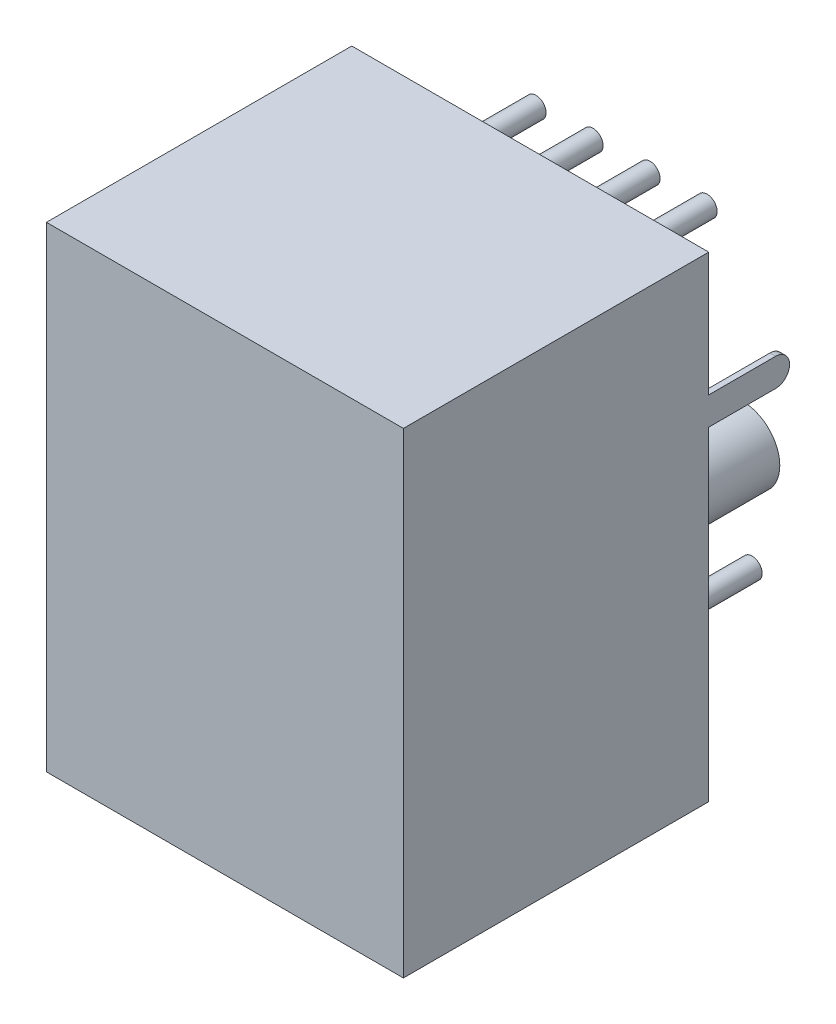
SolidWorks part; units mm, degrees
ref_plane "Front Plane" through (0, 0, 0) normal (0, 0, 1) x (1, 0, 0)
ref_plane "Top Plane" through (0, 0, 0) normal (0, 1, 0) x (1, 0, 0)
ref_plane "Right Plane" through (0, 0, 0) normal (1, 0, 0) x (0, 0, -1)
sketch "Sketch1" plane through (0, 0, 0) normal (0, 1, 0) x (1, 0, 0)
  line L1 (0, 0) -> (15.9, 0)
  line L2 (0, 0) -> (0, 13.6)
  line L3 (0, 13.6) -> (15.9, 13.6)
  line L4 (15.9, 0) -> (15.9, 13.6)
  dimension "D1" = 13.6
  dimension "D2" = 15.9
extrude "Boss-Extrude1" add sketch "Sketch1" along normal blind 21.2
sketch "Sketch2" plane through (0, 0, -13.6) normal (0, 0, -1) x (-1, 0, 0)
  line L0 (-15.9, 0) -> (0, 0) construction
  line L1 (-13.665, 10.8) -> (-2.235, 10.8) construction
  line L2 (-7.95, 0) -> (-7.95, 10.8) construction
  circle A0 centre (-13.665, 10.8) radius 1.65
  circle A1 centre (-2.235, 10.8) radius 1.65
  dimension "D3" = 3.3
  dimension "D1" = 10.8
  dimension "D2" = 11.43
extrude "Boss-Extrude2" add sketch "Sketch2" along normal blind 3.75
sketch "Sketch3" plane through (0, 0, 0) normal (0, -1, 0) x (1, 0, 0)
  line L0 (0, -13.6) -> (0, 0) construction
  line L1 (2.032, -2.54) -> (13.8684, -2.54)
  line L2 (2.032, -2.54) -> (2.032, -9.144)
  line L3 (2.032, -9.144) -> (4.7752, -9.144)
  line L4 (13.8684, -2.54) -> (13.8684, -9.144)
  line L5 (0, 0) -> (15.9, 0) construction
  line L6 (7.9502, -2.54) -> (7.9502, -12.446) construction
  line L8 (4.7752, -9.144) -> (4.7752, -10.922)
  line L9 (4.7752, -10.922) -> (5.9182, -10.922)
  line L10 (11.1252, -9.144) -> (11.1252, -10.922)
  line L12 (5.9182, -10.922) -> (5.9182, -12.446)
  line L13 (5.9182, -12.446) -> (9.9822, -12.446)
  line L14 (9.9822, -10.922) -> (9.9822, -12.446)
  line L15 (11.1252, -9.144) -> (13.8684, -9.144)
  line L16 (9.9822, -10.922) -> (11.1252, -10.922)
  point P20 (7.9502, -12.446)
  dimension "D1" = 2.032
  dimension "D2" = 11.8364
  dimension "D3" = 2.54
  dimension "D4" = 6.604
  dimension "D5" = 6.35
  dimension "D6" = 4.064
  dimension "D7" = 1.524
  dimension "D8" = 1.778
  dimension "D9" = 1.143
extrude "Cut-Extrude1" cut sketch "Sketch3" against normal blind 11.43
sketch "Sketch4" plane through (0, 0, 0) normal (0, -1, 0) x (1, 0, 0)
  line L0 (5.9182, -12.446) -> (9.9822, -12.446) construction
  line L1 (2.032, -2.54) -> (13.8684, -2.54)
  line L2 (2.032, -2.54) -> (2.032, -12.446)
  line L3 (2.032, -12.446) -> (13.8684, -12.446)
  line L4 (13.8684, -2.54) -> (13.8684, -12.446)
  dimension "D1" = 0
  dimension "D2" = 11.8364
extrude "Cut-Extrude2" cut sketch "Sketch4" against normal blind 0.254
sketch "Sketch7" plane through (0, 0, 0) normal (0, -1, 0) x (1, 0, 0)
  line L0 (2.032, -12.446) -> (13.8684, -12.446) construction
  line L1 (1.0668, -12.446) -> (4.5212, -12.446)
  line L2 (1.0668, -12.446) -> (1.0668, -10.414)
  line L3 (1.0668, -10.414) -> (4.5212, -10.414)
  line L4 (4.5212, -12.446) -> (4.5212, -10.414)
  line L5 (14.8336, -12.446) -> (11.3792, -12.446)
  line L6 (14.8336, -12.446) -> (14.8336, -10.414)
  line L7 (14.8336, -10.414) -> (11.3792, -10.414)
  line L8 (11.3792, -12.446) -> (11.3792, -10.414)
  line L9 (4.7752, -10.922) -> (4.7752, -9.144) construction
  line L10 (11.1252, -9.144) -> (11.1252, -10.922) construction
  dimension "D1" = 3.4544
  dimension "D2" = 2.032
  dimension "D3" = 0.254
  dimension "D4" = 0.254
extrude "Cut-Extrude3" cut sketch "Sketch7" against normal blind 1.27
sketch "Sketch8" plane through (0, 1.27, 0) normal (0, -1, 0) x (1, 0, 0)
  line L1 (1.0668, -10.414) -> (4.5212, -10.414)
  line L2 (1.0668, -10.414) -> (1.0668, -12.446)
  line L3 (1.0668, -12.446) -> (4.5212, -12.446)
  line L4 (4.5212, -10.414) -> (4.5212, -12.446)
extrude "Boss-Extrude3" add sketch "Sketch8" along normal blind 1.143 separate body
sketch "Sketch9" plane through (0, 1.27, 0) normal (0, -1, 0) x (1, 0, 0)
  line L1 (11.3792, -10.414) -> (14.8336, -10.414)
  line L2 (11.3792, -10.414) -> (11.3792, -12.446)
  line L3 (11.3792, -12.446) -> (14.8336, -12.446)
  line L4 (14.8336, -10.414) -> (14.8336, -12.446)
extrude "Boss-Extrude4" add sketch "Sketch9" along normal blind 1.143 separate body
sketch "Sketch10" plane through (0, 0, 0) normal (-1, 0, 0) x (0, 0, 1)
  line L0 (-13.6, 14.4479) -> (-16.5777, 14.4479)
  line L1 (-13.6, 21.2) -> (-13.6, 0) construction
  line L2 (-16.5777, 14.4479) -> (-16.5777, 15.6925) construction
  line L3 (-16.5777, 15.6925) -> (-13.6, 15.6925)
  line L4 (-13.6, 15.6925) -> (-13.6, 14.4479)
  line L5 (-13.6, 15.0702) -> (-16.5777, 15.0702) construction
  line L6 (-13.6, 10.8) -> (-17.35, 10.8) construction
  line L7 (-13.6, 12.45) -> (-13.6, 9.15) construction
  line L8 (-17.35, 12.45) -> (-17.35, 9.15) construction
  arc A0 (-16.5777, 15.6925) -> (-16.5777, 14.4479) centre (-16.5777, 15.0702) ccw
  dimension "D1" = 1.2446
  dimension "D2" = 2.9777
extrude "Boss-Extrude5" add sketch "Sketch10" against normal blind 0.254
ref_plane "Plane1" through (7.95, 0, 0) normal (1, 0, 0) x (0, 0, -1)
mirror "Mirror2" about plane through (7.95, 0, 0) normal (1, 0, 0) of "Boss-Extrude5"
sketch "Sketch11" plane through (0, 0, -13.6) normal (0, 0, -1) x (-1, 0, 0)
  line L0 (-15.9, 6.74) -> (0, 6.74) construction
  line L1 (-15.9, 14.4479) -> (-15.9, 0) construction
  line L2 (0, 14.4479) -> (0, 0) construction
  line L3 (-12.04, 6.29) -> (-3.86, 6.29) construction
  line L4 (-14.58, 7.19) -> (-1.32, 7.19) construction
  line L5 (-7.95, 21.2) -> (-7.95, 0) construction
  line L6 (-15.9, 21.2) -> (0, 21.2) construction
  line L7 (-15.9, 0) -> (0, 0) construction
  circle A0 centre (-14.58, 6.74) radius 0.45
  circle A1 centre (-12.04, 6.74) radius 0.45
  circle A2 centre (-3.86, 6.74) radius 0.45
  circle A3 centre (-1.32, 6.74) radius 0.45
  circle A4 centre (-13.665, 10.8) radius 1.65 construction
  point P26 (-7.95, 7.19)
  point P27 (-7.95, 6.29)
  dimension "D2" = 0.9
  dimension "D1" = 4.06
  dimension "D3" = 8.18
  dimension "D4" = 13.26
extrude "Boss-Extrude6" add sketch "Sketch11" along normal blind 3.25
sketch "Sketch12" plane through (0, 0, -13.6) normal (0, 0, -1) x (-1, 0, 0)
  line L0 (0, 19.7) -> (-15.9, 19.7) construction
  line L1 (0, 21.2) -> (0, 15.6925) construction
  line L2 (-15.9, 21.2) -> (-15.9, 15.6925) construction
  line L4 (0, 17.16) -> (-15.9, 17.16) construction
  circle A1 centre (-2.235, 10.8) radius 1.65 construction
  circle A2 centre (-3.685, 17.16) radius 0.45
  circle A3 centre (-6.225, 17.16) radius 0.45
  circle A4 centre (-8.765, 17.16) radius 0.45
  circle A5 centre (-11.305, 17.16) radius 0.45
  circle A6 centre (-4.955, 19.7) radius 0.45
  circle A7 centre (-7.495, 19.7) radius 0.45
  circle A8 centre (-10.035, 19.7) radius 0.45
  circle A9 centre (-12.575, 19.7) radius 0.45
  dimension "D3" = 0.9
  dimension "D1" = 8.9
  dimension "D2" = 2.54
  dimension "D4" = 3.685
  dimension "D5" = 1.27
  dimension "D6" = 1.27
  dimension "D7" = 1.27
  dimension "D8" = 1.27
  dimension "D9" = 1.27
  dimension "D10" = 1.27
  dimension "D11" = 1.27
extrude "Boss-Extrude7" add sketch "Sketch12" along normal blind 3.25
